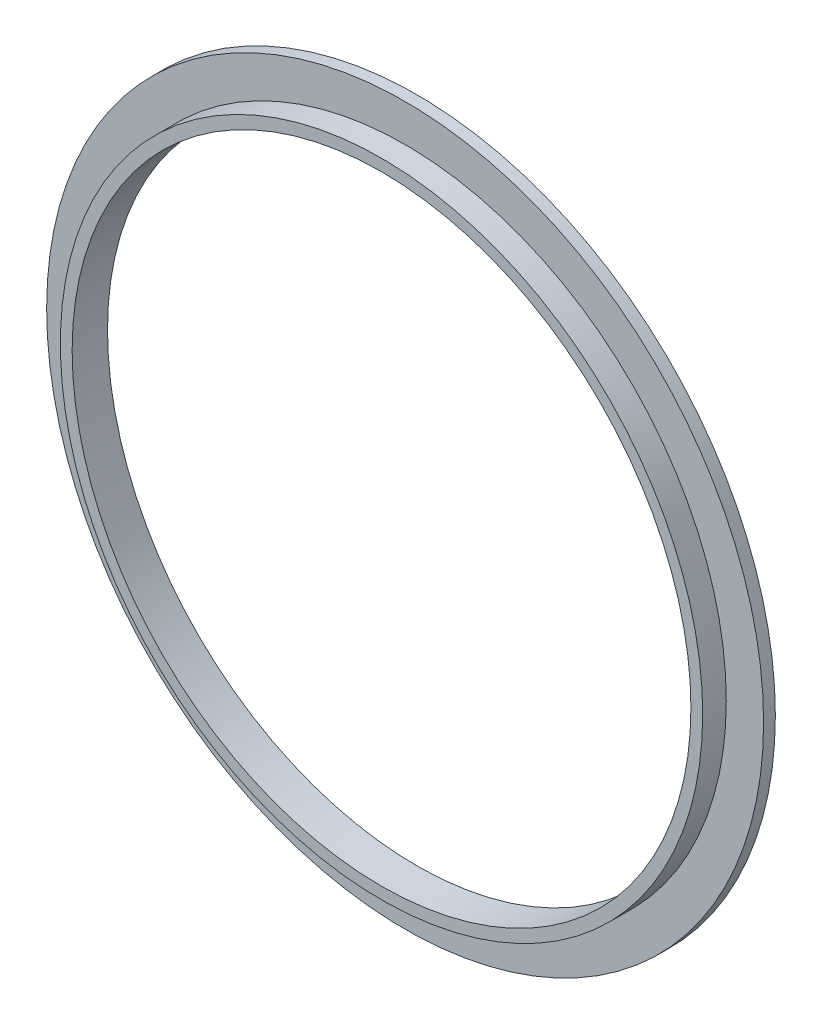
SolidWorks part; units mm, degrees
ref_plane "Front Plane" through (0, 0, 0) normal (0, 0, 1) x (1, 0, 0)
ref_plane "Top Plane" through (0, 0, 0) normal (0, 1, 0) x (1, 0, 0)
ref_plane "Right Plane" through (0, 0, 0) normal (1, 0, 0) x (0, 0, -1)
sketch "Sketch1" plane through (0, 0, 0) normal (0, 0, 1) x (1, 0, 0)
  circle A0 centre (0, 0) radius 54.5
  circle A1 centre (0, 0) radius 52.5
  dimension "D1" = 2
  dimension "D2" = 109
extrude "Boss-Extrude1" add sketch "Sketch1" along normal blind 4
sketch "Sketch2" plane through (0, 0, 0) normal (0, 0, -1) x (-1, 0, 0)
  circle A0 centre (0, 0) radius 60.83
  circle A1 centre (0, 0) radius 52.5 construction
  circle A2 centre (0, 0) radius 52.5
  dimension "D1" = 121.66
extrude "Boss-Extrude2" add sketch "Sketch2" along normal blind 2
